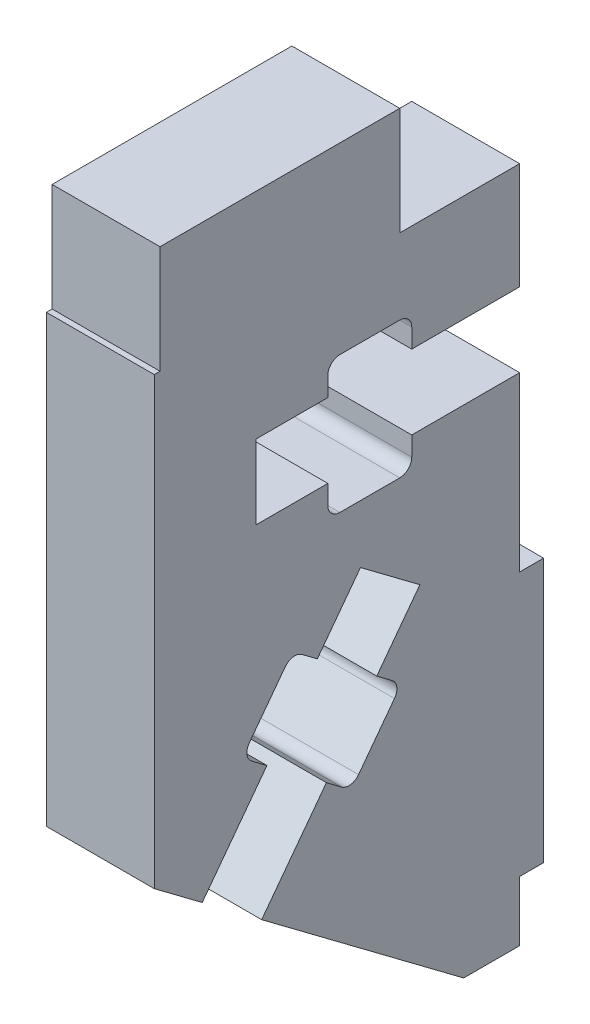
SolidWorks part; units mm, degrees
ref_plane "Front Plane" through (0, 0, 0) normal (0, 0, 1) x (1, 0, 0)
ref_plane "Top Plane" through (0, 0, 0) normal (0, 1, 0) x (1, 0, 0)
ref_plane "Right Plane" through (0, 0, 0) normal (1, 0, 0) x (0, 0, -1)
sketch "Sketch1" plane through (0, 0, 0) normal (1, 0, 0) x (0, 0, -1)
  line L0 (0, 0) -> (0, -30)
  line L1 (0, -30) -> (-40, 0)
  line L2 (-40, 0) -> (0, 0)
  dimension "D1" = 40
  dimension "D2" = 30
extrude "Boss-Extrude1" add sketch "Sketch1" along normal blind 4.5
sketch "Sketch2" plane through (4.5, 0, 0) normal (1, 0, 0) x (0, 0, -1)
  line L0 (0, -25.75) -> (1, -25.75)
  line L1 (0, -30) -> (0, 0) construction
  line L2 (1, -25.75) -> (1, -14.75)
  line L3 (1, -14.75) -> (0, -14.75)
  line L4 (0, -14.75) -> (0, -25.75)
  line L5 (1, -20.25) -> (0, -20.25) construction
  line L6 (0, -14.75) -> (4.5, -14.75) construction
  line L7 (0, -25.75) -> (4.5, -25.75) construction
  dimension "D1" = 0
  dimension "D2" = 1
  dimension "D3" = 0
extrude "Boss-Extrude2" add sketch "Sketch2" against normal through all
sketch "Sketch3" plane through (4.5, 0, 0) normal (1, 0, 0) x (0, 0, -1)
  line L0 (0, -6) -> (-11, -6) construction
  line L1 (0, -14.75) -> (0, 0) construction
  line L2 (-11, -7.55) -> (-11, -4.45) construction
  line L3 (-11, -4.45) -> (0, -4.45) construction
  line L4 (0, -4.45) -> (-4.5, -4.45)
  line L5 (-4.5, -4.45) -> (-4.5, -3.65)
  line L6 (-5, -3.15) -> (-7.5, -3.15)
  line L7 (-8, -3.65) -> (-8, -4.45)
  line L8 (-8, -4.45) -> (-11, -4.45)
  line L9 (-11, -4.45) -> (-11, -7.55)
  line L10 (0, -4.45) -> (0, -7.55)
  line L12 (-11, -7.55) -> (0, -7.55) construction
  line L13 (-8, -7.55) -> (-11, -7.55)
  line L14 (-8, -8.35) -> (-8, -7.55)
  line L15 (-5, -8.85) -> (-7.5, -8.85)
  line L16 (-4.5, -7.55) -> (-4.5, -8.35)
  line L17 (0, -7.55) -> (-4.5, -7.55)
  arc A0 (-4.5, -3.65) -> (-5, -3.15) centre (-5, -3.65) ccw
  arc A1 (-7.5, -3.15) -> (-8, -3.65) centre (-7.5, -3.65) ccw
  arc A2 (-7.5, -8.85) -> (-8, -8.35) centre (-7.5, -8.35) cw
  arc A3 (-4.5, -8.35) -> (-5, -8.85) centre (-5, -8.35) cw
  point P15 (-4.5, -3.15)
  point P18 (-8, -3.15)
  point P29 (-8, -8.85)
  point P30 (-4.5, -8.85)
  dimension "D7" = 0.5
  dimension "D1" = 11
  dimension "D2" = 1.55
  dimension "D3" = 3.5
  dimension "D4" = 2.85
  dimension "D5" = 8
  dimension "D6" = 6
extrude "Cut-Extrude1" cut sketch "Sketch3" against normal through all
sketch "Sketch4" plane through (4.5, 0, 0) normal (1, 0, 0) x (0, 0, -1)
  line L0 (-13.24, -20.07) -> (-6.64, -11.27) construction
  line L1 (-40, 0) -> (0, -30) construction
  line L2 (-6.64, -11.27) -> (-4.16, -13.13) construction
  line L3 (-5.4, -12.2) -> (-12, -21) construction
  line L4 (-10.76, -21.93) -> (-13.24, -20.07)
  line L5 (-13.24, -20.07) -> (-10.54, -16.47)
  line L6 (-10.54, -16.47) -> (-11.18, -15.99)
  line L7 (-11.28, -15.29) -> (-9.78, -13.29)
  line L8 (-9.08, -13.19) -> (-8.44, -13.67)
  line L9 (-8.44, -13.67) -> (-6.64, -11.27)
  line L10 (-6.64, -11.27) -> (-4.16, -13.13)
  line L11 (0, 0) -> (-40, 0) construction
  line L12 (-10.76, -21.93) -> (-4.16, -13.13) construction
  line L13 (-5.96, -15.53) -> (-4.16, -13.13)
  line L14 (-5.32, -16.01) -> (-5.96, -15.53)
  line L15 (-6.72, -18.71) -> (-5.22, -16.71)
  line L16 (-8.06, -18.33) -> (-7.42, -18.81)
  line L17 (-10.76, -21.93) -> (-8.06, -18.33)
  arc A0 (-11.18, -15.99) -> (-11.28, -15.29) centre (-10.88, -15.59) cw
  arc A1 (-9.78, -13.29) -> (-9.08, -13.19) centre (-9.38, -13.59) cw
  arc A2 (-5.22, -16.71) -> (-5.32, -16.01) centre (-5.62, -16.41) ccw
  arc A3 (-7.42, -18.81) -> (-6.72, -18.71) centre (-7.12, -18.41) ccw
  point P14 (-11.58, -15.69)
  point P17 (-9.48, -12.89)
  point P28 (-4.92, -16.31)
  point P29 (-7.02, -19.11)
  dimension "D7" = 0.5
  dimension "D1" = 11
  dimension "D2" = 1.55
  dimension "D3" = 3.5
  dimension "D4" = 2.85
  dimension "D5" = 8
  dimension "D6" = 21
extrude "Cut-Extrude2" cut sketch "Sketch4" against normal through all
sketch "Sketch5" plane through (4.5, 0, 0) normal (1, 0, 0) x (0, 0, -1)
  line L0 (-15.24, -18.57) -> (-15.24, 0)
  line L1 (-40, 0) -> (-13.24, -20.07) construction
  line L2 (0, 0) -> (-40, 0) construction
  line L3 (-15.24, 0) -> (-40, 0)
  line L4 (-40, 0) -> (-15.24, -18.57)
  dimension "D1" = 2
extrude "Cut-Extrude3" cut sketch "Sketch5" against normal through all
sketch "Sketch6" plane through (0, 0, 11) normal (0, 0, -1) x (-1, 0, 0)
  line L0 (-2.25, -4.45) -> (-2.25, -7.55) construction
  line L1 (0, -4.45) -> (-4.5, -4.45) construction
  line L2 (0, -7.55) -> (-4.5, -7.55) construction
  circle A0 centre (-2.25, -6) radius 1.5
  dimension "D1" = 3
sketch "Sketch7" plane through (0, -10.4, 7.8) normal (0, -0.8, 0.6) x (1, 0, 0)
  line L0 (2.25, -1.45) -> (2.25, -4.55) construction
  line L1 (0, -1.45) -> (4.5, -1.45) construction
  line L2 (0, -4.55) -> (4.5, -4.55) construction
  circle A0 centre (2.25, -3) radius 1.55
sketch "Sketch8" plane through (4.5, 0, 0) normal (1, 0, 0) x (0, 0, -1)
  line L0 (-10, 4.5) -> (-10, 0) construction
  line L1 (-15, 0) -> (-5, 0)
  line L2 (-15, 0) -> (-15, 4.5)
  line L3 (-15, 4.5) -> (-5, 4.5)
  line L4 (-5, 0) -> (-5, 4.5)
  line L5 (0, 0) -> (-15.24, 0) construction
  dimension "D1" = 10
  dimension "D2" = 4.5
  dimension "D3" = 10
extrude "Boss-Extrude3" add sketch "Sketch8" against normal through all
sketch "Sketch10" plane through (4.5, 0, 0) normal (1, 0, 0) x (0, 0, -1)
  line L0 (0, -28.25) -> (-2.3333, -28.25)
  line L1 (0, -30) -> (0, -25.75) construction
  line L2 (-10.76, -21.93) -> (0, -30) construction
  line L3 (-2.3333, -28.25) -> (0, -30)
  line L4 (0, -30) -> (0, -28.25)
  dimension "D1" = 0
extrude "Cut-Extrude4" cut sketch "Sketch10" against normal through all contours L0 L3 L4
equation "\"X-ROD-SPACING\"=45"
equation "\"Y-ROD-SPACING\"=75"
equation "\"Z-ROD-SPACING\"=17.5"
equation "\"Y-BED-OFFSET\"=2"
equation "\"Y-BED-ROD-INSET\"=3.5"
equation "\"Y-BED-SCREW-SPACING\"=209"
equation "\"Y-BED-SCREW-CUTOUT-SLOT-HEIGHT\"=2"
equation "\"T-SLOT-NUT-FILLET-RADIUS\"=0.5"
equation "\"T-SLOT-SCREW-SHAFT-RADIUS\"=1.55"
equation "\"T-SLOT-SCREW-SHAFT-CUTOUT-LENGTH\"=11"
equation "\"T-SLOT-NUT-DEPTH\"=3.5"
equation "\"T-SLOT-NUT-WIDTH\"=2.85"
equation "\"T-SLOT-NUT-END-DISTANCE\"=8"
equation "\"ACRYLIC-THICKNESS\"=10"
equation "\"ACRYLIC-THICKNESS2\"=4.5"
equation "\"ACRYLIC-TAB-CUTOUT-SIZE\"=\"ACRYLIC-THICKNESS\"+\"ACRYLIC-TAB-TOLERANCE\"*2"
equation "\"ACRYLIC-TAB-TOLERANCE\"=-.05"
equation "\"ACRYLIC-TAB-WIDTH\"=\"ACRYLIC-THICKNESS\""
equation "\"ACRYLIC-M3-HOLE\"=2.9"
equation "\"SMOOTHROD-CAP-SCREW-DISTANCE\"=20"
equation "\"FRAME-WIDTH-INNER\"=370"
equation "\"NEMA17-HOLE-SPACING\"=31"
equation "\"NEMA17-CENTRAL-CUTOUT\"=22.5"
equation "\"Z-BRACKET-REACH\"=55"
equation "\"Z-ROD-INSET\"=13.5"
equation "\"TOP-BRACKET-SPACING\"=40"
equation "\"SMOOTHROD-X-LENGTH\"=350"
equation "\"SMOOTHROD-Y-LENGTH\"=350"
equation "\"SMOOTHROD-Z-LENGTH\"=350"
equation "\"SMOOTHROD-TIGHTENING-HEADROOM\"=.25"
equation "\"LEADSCREW-Z-LENGTH\"=300"
equation "\"SCREW-LENGTH-FRAME\"=\"ACRYLIC-THICKNESS\" + 10"
equation "\"SCREW-LENGTH-MOTOR\"=\"ACRYLIC-THICKNESS\" + 5"
equation "\"SCREW-LENGTH-EXTRUDER\"=28"
equation "\"SCREW-HEAD-RADIUS\"=6"
equation "\"PRINTED-M3-HOLE\"=3.5"
equation "\"PRINTED-X-SMOOTHROD-DIAMETER\"=8.8"
equation "\"PRINTED-X-SMOOTHROD-CUTOUT\"=10"
equation "\"PRINTED-X-BASE-HEIGHT\"=10"
equation "\"PRINTED-LM8UU-CUTOUT-SIZE\"=15.5"
equation "\"PRINTED-LM8UU-CUTOUT-LENGTH\"=24.5"
equation "\"PRINTED-X-IDLER-HEIGHT\"=16"
equation "\"PRINTED-M3-NUT-AF\"=6.25"
equation "\"PSU-MOUNTING-WIDTH\"=95"
equation "\"PSU-MOUNTING-HEIGHT\"=177"
equation "\"Y-BELT-TO-ROD-DISTANCE\"=20"
equation "\"SPOOL-HOLDER-ROD-SPACING\"=150"
equation "\"ACRYLIC-X-CARRIAGE-WIDTH\"=55"
equation "\"ACRYLIC-X-CARRIAGE-HEIGHT\"=75"
equation "\"ACRYLIC-X-CARRIAGE-LM8UU-CUTOUT-WIDTH\"=24.25"
equation "\"ACRYLIC-X-CARRIAGE-LM8UU-CUTOUT-HEIGHT\"=11.0"
equation "\"ACRYLIC-X-CARRIAGE-SCREW-SPACING-X\"=15"
equation "\"ACRYLIC-X-CARRIAGE-SCREW-SPACING-Y\"=33"
equation "\"ACRYLIC-X-CARRIAGE-CENTER-TAB-SPACING\"=14"
equation "\"ACRYLIC-X-CARRIAGE-EXTRUDER-OFFSET\"=26"
equation "\"ACRYLIC-X-CARRIAGE-EXTRUDER-ANGLE\"=90"
equation "\"ACRYLIC-X-CARRIAGE-EXTRUDER-SHELF-DEPTH\"=\"ACRYLIC-X-CARRIAGE-EXTRUDER-OFFSET\" + 28"
equation "\"ACRYLIC-X-CARRIAGE-EXTRUDER-BRACE-SPACING\"=23"
equation "\"ACRYLIC-X-CARRIAGE-EXTRUDER-BRACE-TAB-OFFSET\"=20"
equation "\"ACRYLIC-X-CARRIAGE-EXTRUDER-BRACE-HEIGHT\"=35"
equation "\"ACRYLIC-X-CARRIAGE-EXTRUDER-BRACE-SCREW-SPACING\"=22"
equation "\"ACRYLIC-X-CARRIAGE-DUAL-WIDTH-MULTIPLIER\"=1.65"
equation "\"ACRYLIC-X-CARRIAGE-DUAL-HOTEND-SPACING\"=42"
equation "\"ACRYLIC-X-CARRIAGE-DUAL-WIDTH\"=75"
equation "\"ACRYLIC-X-CARRIAGE-DUAL-FAN-OFFSET\"=52"
equation "\"ACRYLIC-X-CARRIAGE-DUAL-FAN-HEIGHT\"=20"
equation "\"ACRYLIC-X-CARRIAGE-DUAL-HOTEND-SEPARATION\"=36"
equation "\"ACRYLIC-X-CARRIAGE-DUAL-MOUNT-PLATE-DEPTH\"=75"
equation "\"ACRYLIC-X-CARRIAGE-DUAL-MOUNT-BRACE-WIDTH\"=33"
equation "\"ACRYLIC-X-CARRIAGE-DUAL-MOUNT-SCREW-WIDTH\"=40"
equation "\"BLOWER-FAN-WIDTH\"=15"
equation "\"D1@Boss-Extrude1\"=\"ACRYLIC-THICKNESS2\""
equation "\"D1@Sketch3\"=\"T-SLOT-SCREW-SHAFT-CUTOUT-LENGTH\""
equation "\"D2@Sketch3\"=\"T-SLOT-SCREW-SHAFT-RADIUS\""
equation "\"D3@Sketch3\"=\"T-SLOT-NUT-DEPTH\""
equation "\"D4@Sketch3\"=\"T-SLOT-NUT-WIDTH\""
equation "\"D5@Sketch3\"=\"T-SLOT-NUT-END-DISTANCE\""
equation "\"D7@Sketch3\"=\"T-SLOT-NUT-FILLET-RADIUS\""
equation "\"D1@Sketch4\"=\"T-SLOT-SCREW-SHAFT-CUTOUT-LENGTH\""
equation "\"D2@Sketch4\"=\"T-SLOT-SCREW-SHAFT-RADIUS\""
equation "\"D3@Sketch4\"=\"T-SLOT-NUT-DEPTH\""
equation "\"D4@Sketch4\"=\"T-SLOT-NUT-WIDTH\""
equation "\"D5@Sketch4\"=\"T-SLOT-NUT-END-DISTANCE\""
equation "\"D7@Sketch4\"=\"T-SLOT-NUT-FILLET-RADIUS\""
equation "\"D1@Sketch8\"=\"ACRYLIC-TAB-WIDTH\""
equation "\"D2@Sketch8\"=\"ACRYLIC-THICKNESS2\""
